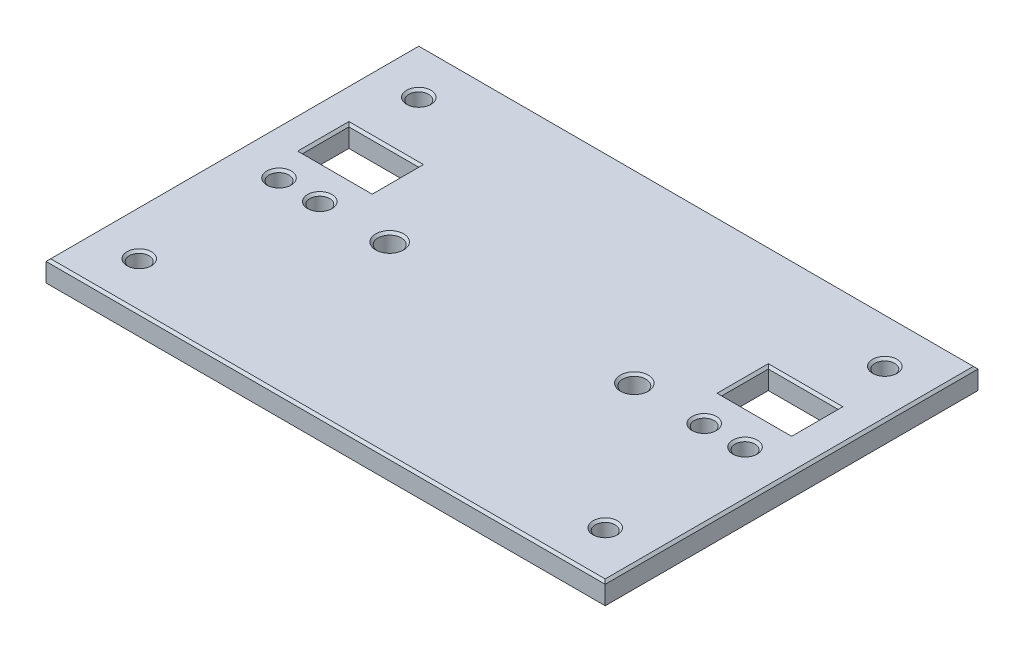
SolidWorks part; units mm, degrees
ref_plane "Front Plane" through (0, 0, 0) normal (0, 0, 1) x (1, 0, 0)
ref_plane "Top Plane" through (0, 0, 0) normal (0, 1, 0) x (1, 0, 0)
ref_plane "Right Plane" through (0, 0, 0) normal (1, 0, 0) x (0, 0, -1)
sketch "Sketch1" plane through (0, 0, 0) normal (0, 1, 0) x (1, 0, 0)
  line L0 (-60, 0) -> (60, 0) construction
  line L1 (-60, -40) -> (60, -40)
  line L2 (-60, -40) -> (-60, 40)
  line L3 (-60, 40) -> (60, 40)
  line L4 (60, -40) -> (60, 40)
  line L5 (-60, -40) -> (60, 40) construction
  line L6 (-60, 40) -> (60, -40) construction
  line L7 (0, 40) -> (0, -40) construction
  circle A0 centre (-50, 30) radius 2.125
  circle A1 centre (-50, -30) radius 2.125
  circle A2 centre (50, -30) radius 2.125
  circle A3 centre (50, 30) radius 2.125
  circle A4 centre (-26.25, 0) radius 2.5
  circle A6 centre (26.25, 0) radius 2.5
  circle A7 centre (-50, 0) radius 2.125
  circle A8 centre (50, 0) radius 2.125
  circle A9 centre (41.25, 0) radius 2.125
  circle A10 centre (-41.25, 0) radius 2.125
  point P0 (0, 0)
  dimension "D5" = 4.25
  dimension "D6" = 5
  dimension "D7" = 52.5
  dimension "D8" = 4.25
  dimension "D9" = 4.25
  dimension "D1" = 80
  dimension "D2" = 120
  dimension "D3" = 10
  dimension "D4" = 10
  dimension "D10" = 18.75
extrude "Boss-Extrude1" add sketch "Sketch1" along normal blind 5
sketch "Sketch3" plane through (0, 0, 0) normal (0, -1, 0) x (1, 0, 0)
  line L0 (0, 0) -> (0, -40) construction
  line L12 (37.5, -7.5) -> (52.5, -7.5)
  line L13 (37.5, -7.5) -> (37.5, -17.5)
  line L14 (37.5, -17.5) -> (52.5, -17.5)
  line L15 (52.5, -7.5) -> (52.5, -17.5)
  line L16 (37.5, -7.5) -> (52.5, -17.5) construction
  line L17 (37.5, -17.5) -> (52.5, -7.5) construction
  line L18 (60, -40) -> (-60, -40) construction
  line L19 (-37.5, -17.5) -> (-52.5, -17.5)
  line L20 (-52.5, -7.5) -> (-52.5, -17.5)
  line L21 (-37.5, -7.5) -> (-52.5, -7.5)
  line L22 (-37.5, -7.5) -> (-37.5, -17.5)
  point P0 (45, -12.5)
  dimension "D1" = 12.5
  dimension "D2" = 45
  dimension "D3" = 10
  dimension "D4" = 15
extrude "Cut-Extrude1" cut sketch "Sketch3" against normal up to surface (5 mm away) up to face at (0, 5, 0)
chamfer "Chamfer2" distance 0.5 angle 45 22 edges at (50, 5, -2.125) (-50, 5, 2.125) (26.25, 5, -2.5) (-26.25, 5, 2.5) (50, 5, -32.125) (-50, 5, 27.875) (50, 5, 32.125) (-50, 5, -27.875) (0, 5, 40) (-60, 5, 0) (0, 5, -40) (60, 5, 0) (37.5, 5, -12.5) (45, 5, -7.5) (52.5, 5, -12.5) (45, 5, -17.5) (41.25, 5, 2.125) (-41.25, 5, -2.125) (-52.5, 5, -12.5) (-45, 5, -7.5) (-37.5, 5, -12.5) (-45, 5, -17.5)
chamfer "Chamfer3" distance 0.5 angle 45 22 edges at (50, 0, -2.125) (26.25, 0, -2.5) (50, 0, -32.125) (50, 0, 32.125) (0, 0, -40) (-60, 0, 0) (0, 0, 40) (60, 0, 0) (-50, 0, -27.875) (-50, 0, 27.875) (-26.25, 0, 2.5) (-50, 0, 2.125) (45, 0, -7.5) (37.5, 0, -12.5) (45, 0, -17.5) (52.5, 0, -12.5) (41.25, 0, 2.125) (-41.25, 0, -2.125) (-45, 0, -7.5) (-52.5, 0, -12.5) (-45, 0, -17.5) (-37.5, 0, -12.5)
